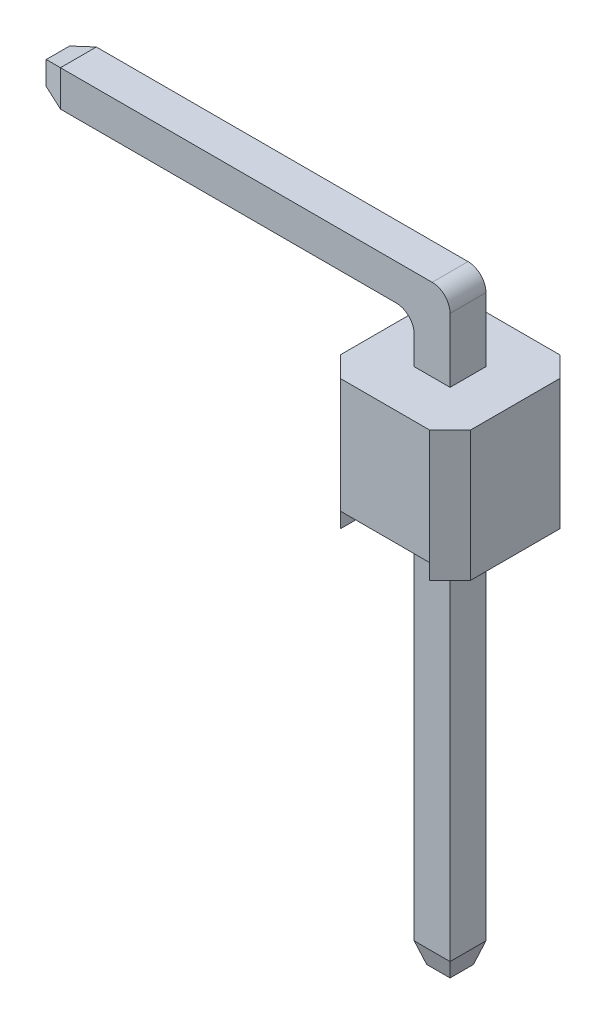
SolidWorks part; units mm, degrees
ref_plane "Front Plane" through (0, 0, 0) normal (0, 0, 1) x (1, 0, 0)
ref_plane "Top Plane" through (0, 0, 0) normal (0, 1, 0) x (1, 0, 0)
ref_plane "Right Plane" through (0, 0, 0) normal (1, 0, 0) x (0, 0, -1)
sketch "Sketch1" plane through (0, 0, 0) normal (0, 1, 0) x (1, 0, 0)
  line L1 (-1.27, 1.27) -> (1.27, 1.27)
  line L2 (-1.27, 1.27) -> (-1.27, -1.27)
  line L3 (-1.27, -1.27) -> (1.27, -1.27)
  line L4 (1.27, 1.27) -> (1.27, -1.27)
  line L5 (-1.27, 1.27) -> (1.27, -1.27) construction
  line L6 (-1.27, -1.27) -> (1.27, 1.27) construction
  point P0 (0, 0)
  dimension "D1" = 2.54
  dimension "D2" = 2.54
extrude "Boss-Extrude1" add sketch "Sketch1" along normal blind 2.54
chamfer "Chamfer1" distance 0.4 angle 45 4 edges at (-1.27, 1.27, -1.27) (1.27, 1.27, -1.27) (-1.27, 1.27, 1.27) (1.27, 1.27, 1.27)
sketch "Sketch2" plane through (0, 0, 0) normal (0, -1, 0) x (1, 0, 0)
  line L1 (-0.87, 1.27) -> (0.87, 1.27)
  line L2 (-0.87, 1.27) -> (-0.87, -1.27)
  line L3 (-0.87, -1.27) -> (0.87, -1.27)
  line L4 (0.87, 1.27) -> (0.87, -1.27)
extrude "Cut-Extrude1" cut sketch "Sketch2" against normal blind 0.3
sketch "Sketch3" plane through (0, 2.54, 0) normal (0, 1, 0) x (1, 0, 0)
  line L1 (0.35, 0.35) -> (-0.35, 0.35)
  line L2 (0.35, 0.35) -> (0.35, -0.35)
  line L3 (0.35, -0.35) -> (-0.35, -0.35)
  line L4 (-0.35, 0.35) -> (-0.35, -0.35)
  line L5 (0.35, 0.35) -> (-0.35, -0.35) construction
  line L6 (0.35, -0.35) -> (-0.35, 0.35) construction
  point P0 (0, 0)
  dimension "D1" = 0.7
  dimension "D2" = 0.7
extrude "Boss-Extrude2" add sketch "Sketch3" along normal blind 1.6
sketch "Sketch5" plane through (-0.35, 0, 0) normal (-1, 0, 0) x (0, 0, 1)
  line L0 (0.35, 4.14) -> (0.35, 2.54) construction
  line L1 (-0.35, 4.14) -> (0.35, 4.14)
  line L2 (-0.35, 4.14) -> (-0.35, 3.44)
  line L3 (-0.35, 3.44) -> (0.35, 3.44)
  line L4 (0.35, 4.14) -> (0.35, 3.44)
extrude "Boss-Extrude4" add sketch "Sketch5" along normal blind 7.3
sketch "Sketch4" plane through (0, 0.3, 0) normal (0, -1, 0) x (1, 0, 0)
  line L1 (-0.35, 0.35) -> (0.35, 0.35) construction
  line L2 (0.35, 0.35) -> (-0.35, 0.35)
  line L3 (0.35, 0.35) -> (0.35, -0.35)
  line L4 (0.35, -0.35) -> (-0.35, -0.35)
  line L5 (-0.35, 0.35) -> (-0.35, -0.35)
  line L6 (0.35, 0.35) -> (-0.35, -0.35) construction
  line L7 (0.35, -0.35) -> (-0.35, 0.35) construction
  point P0 (0, 0)
extrude "Boss-Extrude3" add sketch "Sketch4" along normal offset from surface (7.86 mm away) 11.7
chamfer "Chamfer2" distance 0.4 angle 17 8 edges at (-7.65, 4.14, 0) (-7.65, 3.79, 0.35) (-7.65, 3.44, 0) (-7.65, 3.79, -0.35) (0.35, -7.56, 0) (0, -7.56, -0.35) (-0.35, -7.56, 0) (0, -7.56, 0.35)
fillet "Fillet1" radius 0.35 2 edges at (-0.35, 3.44, 0) (0.35, 4.14, 0)
